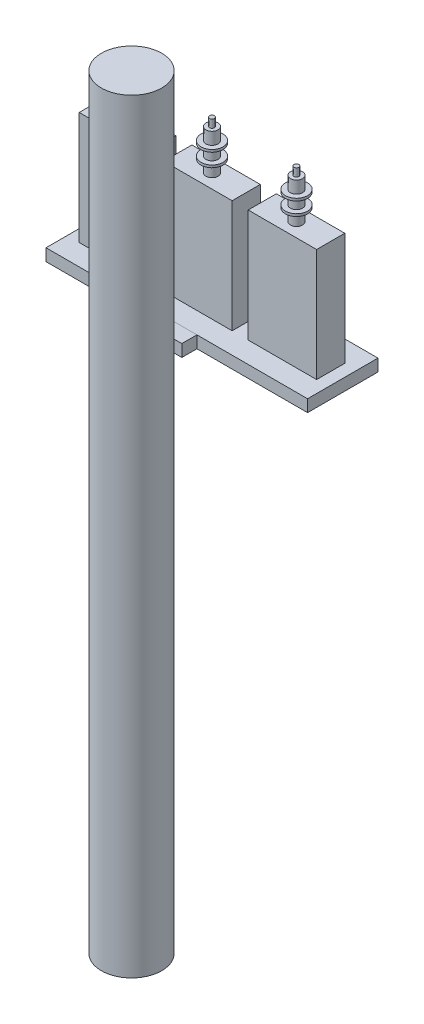
SolidWorks part; units mm, degrees
ref_plane "Front Plane" through (0, 0, 0) normal (0, 0, 1) x (1, 0, 0)
ref_plane "Top Plane" through (0, 0, 0) normal (0, 1, 0) x (1, 0, 0)
ref_plane "Right Plane" through (0, 0, 0) normal (1, 0, 0) x (0, 0, -1)
sketch "Sketch1" plane through (0, 0, 0) normal (0, 1, 0) x (1, 0, 0)
  line L1 (-650, -175) -> (650, -175)
  line L2 (-650, -175) -> (-650, 175)
  line L3 (-650, 175) -> (650, 175)
  line L4 (650, -175) -> (650, 175)
  line L5 (-650, -175) -> (650, 175) construction
  line L6 (-650, 175) -> (650, -175) construction
  point P0 (0, 0)
extrude "Rack" add sketch "Sketch1" along normal blind 60 from offset 60 separate body
sketch "Sketch2" plane through (0, 0, 0) normal (0, 1, 0) x (1, 0, 0)
  line L0 (-650, -175) -> (650, -175) construction
  line L1 (-100, -250) -> (100, -250)
  line L2 (-100, -250) -> (-100, -175)
  line L3 (-100, -175) -> (100, -175)
  line L4 (100, -250) -> (100, -175)
  line L5 (-100, -250) -> (100, -175) construction
  line L6 (-100, -175) -> (100, -250) construction
  point P0 (0, -212.5)
extrude "Rack arm" add sketch "Sketch2" along normal blind 60 from offset 60 separate body
sketch "Sketch3" plane through (0, 0, 0) normal (0, 1, 0) x (1, 0, 0)
  circle A0 centre (0, -400) radius 150
extrude "Pole" add sketch "Sketch3" along normal blind 3800 from offset 2600 separate body
sketch "Sketch4" plane through (0, 0, 0) normal (0, 1, 0) x (1, 0, 0)
  line L1 (-590, -70) -> (-250, -70)
  line L2 (-590, -70) -> (-590, 70)
  line L3 (-590, 70) -> (-250, 70)
  line L4 (-250, -70) -> (-250, 70)
  line L5 (-590, -70) -> (-250, 70) construction
  line L6 (-590, 70) -> (-250, -70) construction
  point P0 (-420, 0)
extrude "Capacitor can A" add sketch "Sketch4" along normal blind 560 separate body
sketch "Sketch5" plane through (0, 0, 0) normal (0, 1, 0) x (1, 0, 0)
  circle A0 centre (-420, 0) radius 30
extrude "Bushing A" add sketch "Sketch5" along normal blind 200 from offset 560 separate body
sketch "Sketch6" plane through (0, 0, 0) normal (0, 1, 0) x (1, 0, 0)
  circle A0 centre (-420, 0) radius 55
extrude "Shed A 1" add sketch "Sketch6" along normal blind 12 from offset 620.6667 separate body
sketch "Sketch7" plane through (0, 0, 0) normal (0, 1, 0) x (1, 0, 0)
  circle A0 centre (-420, 0) radius 55
extrude "Shed A 2" add sketch "Sketch7" along normal blind 12 from offset 687.3333 separate body
sketch "Sketch8" plane through (0, 0, 0) normal (0, 1, 0) x (1, 0, 0)
  circle A0 centre (-420, 0) radius 12
extrude "Terminal A" add sketch "Sketch8" along normal blind 40 from offset 760 separate body
sketch "Sketch9" plane through (0, 0, 0) normal (0, 1, 0) x (1, 0, 0)
  line L1 (-170, -70) -> (170, -70)
  line L2 (-170, -70) -> (-170, 70)
  line L3 (-170, 70) -> (170, 70)
  line L4 (170, -70) -> (170, 70)
  line L5 (-170, -70) -> (170, 70) construction
  line L6 (-170, 70) -> (170, -70) construction
  point P0 (0, 0)
extrude "Capacitor can B" add sketch "Sketch9" along normal blind 560 separate body
sketch "Sketch10" plane through (0, 0, 0) normal (0, 1, 0) x (1, 0, 0)
  circle A0 centre (0, 0) radius 30
extrude "Bushing B" add sketch "Sketch10" along normal blind 200 from offset 560 separate body
sketch "Sketch11" plane through (0, 0, 0) normal (0, 1, 0) x (1, 0, 0)
  circle A0 centre (0, 0) radius 55
extrude "Shed B 1" add sketch "Sketch11" along normal blind 12 from offset 620.6667 separate body
sketch "Sketch12" plane through (0, 0, 0) normal (0, 1, 0) x (1, 0, 0)
  circle A0 centre (0, 0) radius 55
extrude "Shed B 2" add sketch "Sketch12" along normal blind 12 from offset 687.3333 separate body
sketch "Sketch13" plane through (0, 0, 0) normal (0, 1, 0) x (1, 0, 0)
  circle A0 centre (0, 0) radius 12
extrude "Terminal B" add sketch "Sketch13" along normal blind 40 from offset 760 separate body
sketch "Sketch14" plane through (0, 0, 0) normal (0, 1, 0) x (1, 0, 0)
  line L1 (250, -70) -> (590, -70)
  line L2 (250, -70) -> (250, 70)
  line L3 (250, 70) -> (590, 70)
  line L4 (590, -70) -> (590, 70)
  line L5 (250, -70) -> (590, 70) construction
  line L6 (250, 70) -> (590, -70) construction
  point P0 (420, 0)
extrude "Capacitor can C" add sketch "Sketch14" along normal blind 560 separate body
sketch "Sketch15" plane through (0, 0, 0) normal (0, 1, 0) x (1, 0, 0)
  circle A0 centre (420, 0) radius 30
extrude "Bushing C" add sketch "Sketch15" along normal blind 200 from offset 560 separate body
sketch "Sketch16" plane through (0, 0, 0) normal (0, 1, 0) x (1, 0, 0)
  circle A0 centre (420, 0) radius 55
extrude "Shed C 1" add sketch "Sketch16" along normal blind 12 from offset 620.6667 separate body
sketch "Sketch17" plane through (0, 0, 0) normal (0, 1, 0) x (1, 0, 0)
  circle A0 centre (420, 0) radius 55
extrude "Shed C 2" add sketch "Sketch17" along normal blind 12 from offset 687.3333 separate body
sketch "Sketch18" plane through (0, 0, 0) normal (0, 1, 0) x (1, 0, 0)
  circle A0 centre (420, 0) radius 12
extrude "Terminal C" add sketch "Sketch18" along normal blind 40 from offset 760 separate body
